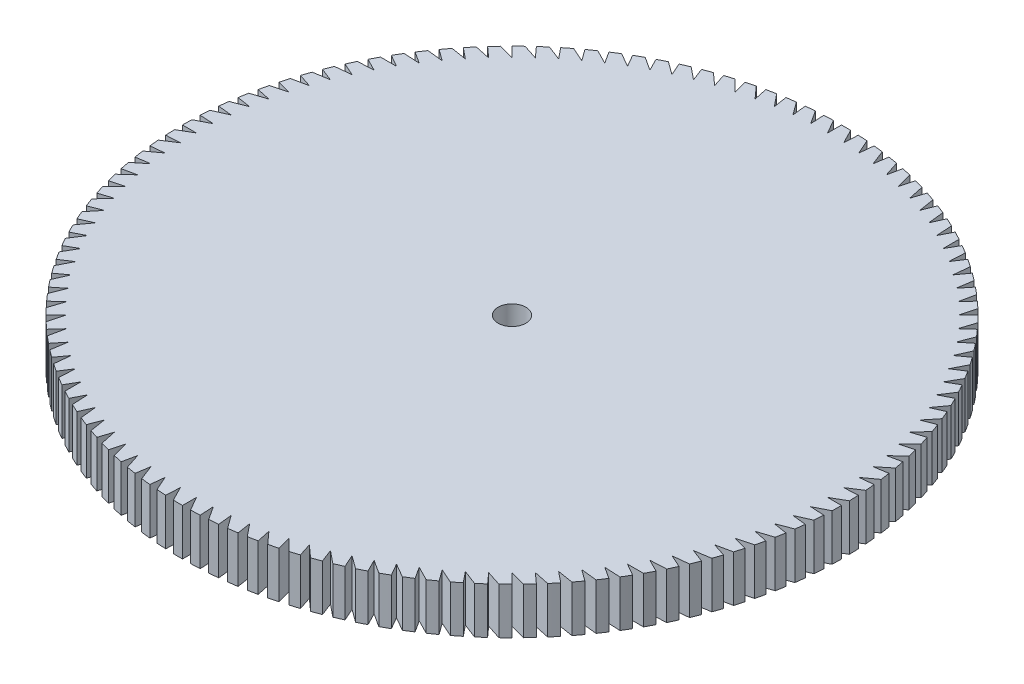
SolidWorks part; units mm, degrees
ref_plane "前视基准面" through (0, 0, 0) normal (0, 0, 1) x (1, 0, 0)
ref_plane "上视基准面" through (0, 0, 0) normal (0, 1, 0) x (1, 0, 0)
ref_plane "右视基准面" through (0, 0, 0) normal (1, 0, 0) x (0, 0, -1)
sketch "草图1" plane through (0, 0, 0) normal (0, 1, 0) x (1, 0, 0)
  circle A0 centre (0, 0) radius 71
  dimension "D1" = 142
extrude "凸台-拉伸1" add sketch "草图1" along normal blind 10
sketch "草图2" plane through (0, 10, 0) normal (0, 1, 0) x (1, 0, 0)
  circle A0 centre (0, 0) radius 3
  dimension "D1" = 6
extrude "切除-拉伸1" cut sketch "草图2" against normal blind 10
sketch "草图3" plane through (0, 10, 0) normal (0, 1, 0) x (1, 0, 0)
  line L0 (0, -71) -> (0, -68)
  line L1 (0, -68) -> (1.72, -70.9792)
  line L2 (-3.5588, -67.9068) -> (-1.9971, -70.9719)
  line L3 (-3.7159, -70.9027) -> (-3.5588, -67.9068)
  line L4 (-7.1079, -67.6275) -> (-5.7087, -70.7701)
  line L5 (-7.4215, -70.6111) -> (-7.1079, -67.6275)
  line L6 (-10.6375, -67.1628) -> (-9.4047, -70.3744)
  line L7 (-11.1068, -70.1259) -> (-10.6375, -67.1628)
  line L8 (-14.138, -66.514) -> (-13.075, -69.7857)
  line L9 (-14.7617, -69.4485) -> (-14.138, -66.514)
  line L10 (-17.5997, -65.683) -> (-16.7093, -69.0058)
  line L11 (-18.3762, -68.5807) -> (-17.5997, -65.683)
  line L12 (-21.0132, -64.6718) -> (-20.2979, -68.0367)
  line L13 (-21.9402, -67.525) -> (-21.0132, -64.6718)
  line L14 (-24.369, -63.4835) -> (-23.8309, -66.8812)
  line L15 (-25.4441, -66.2842) -> (-24.369, -63.4835)
  line L16 (-27.6581, -62.1211) -> (-27.2985, -65.5423)
  line L17 (-28.8783, -64.8617) -> (-27.6581, -62.1211)
  line L18 (-30.8714, -60.5884) -> (-30.6913, -64.0238)
  line L19 (-32.2333, -63.2615) -> (-30.8714, -60.5884)
  line L20 (-34, -58.8897) -> (-34, -62.3298)
  line L21 (-35.5, -61.4878) -> (-34, -58.8897)
  line L22 (-37.0355, -57.0296) -> (-37.2155, -60.4649)
  line L23 (-38.6694, -59.5456) -> (-37.0355, -57.0296)
  line L24 (-39.9694, -55.0132) -> (-40.329, -58.4344)
  line L25 (-41.7328, -57.4402) -> (-39.9694, -55.0132)
  line L26 (-42.7938, -52.8459) -> (-43.3319, -56.2436)
  line L27 (-44.6817, -55.1774) -> (-42.7938, -52.8459)
  line L28 (-45.5009, -50.5338) -> (-46.2161, -53.8987)
  line L29 (-47.5083, -52.7633) -> (-45.5009, -50.5338)
  line L30 (-48.0833, -48.0833) -> (-48.9736, -51.4061)
  line L31 (-50.2046, -50.2046) -> (-48.0833, -48.0833)
  line L32 (-50.5338, -45.5009) -> (-51.5969, -48.7726)
  line L33 (-52.7633, -47.5083) -> (-50.5338, -45.5009)
  line L34 (-52.8459, -42.7938) -> (-54.0787, -46.0053)
  line L35 (-55.1774, -44.6817) -> (-52.8459, -42.7938)
  line L36 (-55.0132, -39.9694) -> (-56.4123, -43.112)
  line L37 (-57.4402, -41.7328) -> (-55.0132, -39.9694)
  line L38 (-57.0296, -37.0355) -> (-58.5913, -40.1006)
  line L39 (-59.5456, -38.6694) -> (-57.0296, -37.0355)
  line L40 (-58.8897, -34) -> (-60.6097, -36.9792)
  line L41 (-61.4878, -35.5) -> (-58.8897, -34)
  line L42 (-60.5884, -30.8714) -> (-62.462, -33.7564)
  line L43 (-63.2615, -32.2333) -> (-60.5884, -30.8714)
  line L44 (-62.1211, -27.6581) -> (-64.1431, -30.4411)
  line L45 (-64.8617, -28.8783) -> (-62.1211, -27.6581)
  line L46 (-63.4835, -24.369) -> (-65.6484, -27.0424)
  line L47 (-66.2842, -25.4441) -> (-63.4835, -24.369)
  line L48 (-64.6718, -21.0132) -> (-66.9737, -23.5696)
  line L49 (-67.525, -21.9402) -> (-64.6718, -21.0132)
  line L50 (-65.683, -17.5997) -> (-68.1154, -20.0322)
  line L51 (-68.5807, -18.3762) -> (-65.683, -17.5997)
  line L52 (-66.514, -14.138) -> (-69.0705, -16.4398)
  line L53 (-69.4485, -14.7617) -> (-66.514, -14.138)
  line L54 (-67.1628, -10.6375) -> (-69.8362, -12.8024)
  line L55 (-70.1259, -11.1068) -> (-67.1628, -10.6375)
  line L56 (-67.6275, -7.1079) -> (-70.4105, -9.1299)
  line L57 (-70.6111, -7.4215) -> (-67.6275, -7.1079)
  line L58 (-67.9068, -3.5588) -> (-70.7919, -5.4324)
  line L59 (-70.9027, -3.7159) -> (-67.9068, -3.5588)
  line L60 (-68, 0) -> (-70.9792, -1.72)
  line L61 (-71, 0) -> (-68, 0)
  line L62 (-67.9068, 3.5588) -> (-70.9719, 1.9971)
  line L63 (-70.9027, 3.7159) -> (-67.9068, 3.5588)
  line L64 (-67.6275, 7.1079) -> (-70.7701, 5.7087)
  line L65 (-70.6111, 7.4215) -> (-67.6275, 7.1079)
  line L66 (-67.1628, 10.6375) -> (-70.3744, 9.4047)
  line L67 (-70.1259, 11.1068) -> (-67.1628, 10.6375)
  line L68 (-66.514, 14.138) -> (-69.7857, 13.075)
  line L69 (-69.4485, 14.7617) -> (-66.514, 14.138)
  line L70 (-65.683, 17.5997) -> (-69.0058, 16.7093)
  line L71 (-68.5807, 18.3762) -> (-65.683, 17.5997)
  line L72 (-64.6718, 21.0132) -> (-68.0367, 20.2979)
  line L73 (-67.525, 21.9402) -> (-64.6718, 21.0132)
  line L74 (-63.4835, 24.369) -> (-66.8812, 23.8309)
  line L75 (-66.2842, 25.4441) -> (-63.4835, 24.369)
  line L76 (-62.1211, 27.6581) -> (-65.5423, 27.2985)
  line L77 (-64.8617, 28.8783) -> (-62.1211, 27.6581)
  line L78 (-60.5884, 30.8714) -> (-64.0238, 30.6913)
  line L79 (-63.2615, 32.2333) -> (-60.5884, 30.8714)
  line L80 (-58.8897, 34) -> (-62.3298, 34)
  line L81 (-61.4878, 35.5) -> (-58.8897, 34)
  line L82 (-57.0296, 37.0355) -> (-60.4649, 37.2155)
  line L83 (-59.5456, 38.6694) -> (-57.0296, 37.0355)
  line L84 (-55.0132, 39.9694) -> (-58.4344, 40.329)
  line L85 (-57.4402, 41.7328) -> (-55.0132, 39.9694)
  line L86 (-52.8459, 42.7938) -> (-56.2436, 43.3319)
  line L87 (-55.1774, 44.6817) -> (-52.8459, 42.7938)
  line L88 (-50.5338, 45.5009) -> (-53.8987, 46.2161)
  line L89 (-52.7633, 47.5083) -> (-50.5338, 45.5009)
  line L90 (-48.0833, 48.0833) -> (-51.4061, 48.9736)
  line L91 (-50.2046, 50.2046) -> (-48.0833, 48.0833)
  line L92 (-45.5009, 50.5338) -> (-48.7726, 51.5969)
  line L93 (-47.5083, 52.7633) -> (-45.5009, 50.5338)
  line L94 (-42.7938, 52.8459) -> (-46.0053, 54.0787)
  line L95 (-44.6817, 55.1774) -> (-42.7938, 52.8459)
  line L96 (-39.9694, 55.0132) -> (-43.112, 56.4123)
  line L97 (-41.7328, 57.4402) -> (-39.9694, 55.0132)
  line L98 (-37.0355, 57.0296) -> (-40.1006, 58.5913)
  line L99 (-38.6694, 59.5456) -> (-37.0355, 57.0296)
  line L100 (-34, 58.8897) -> (-36.9792, 60.6097)
  line L101 (-35.5, 61.4878) -> (-34, 58.8897)
  line L102 (-30.8714, 60.5884) -> (-33.7564, 62.462)
  line L103 (-32.2333, 63.2615) -> (-30.8714, 60.5884)
  line L104 (-27.6581, 62.1211) -> (-30.4411, 64.1431)
  line L105 (-28.8783, 64.8617) -> (-27.6581, 62.1211)
  line L106 (-24.369, 63.4835) -> (-27.0424, 65.6484)
  line L107 (-25.4441, 66.2842) -> (-24.369, 63.4835)
  line L108 (-21.0132, 64.6718) -> (-23.5696, 66.9737)
  line L109 (-21.9402, 67.525) -> (-21.0132, 64.6718)
  line L110 (-17.5997, 65.683) -> (-20.0322, 68.1154)
  line L111 (-18.3762, 68.5807) -> (-17.5997, 65.683)
  line L112 (-14.138, 66.514) -> (-16.4398, 69.0705)
  line L113 (-14.7617, 69.4485) -> (-14.138, 66.514)
  line L114 (-10.6375, 67.1628) -> (-12.8024, 69.8362)
  line L115 (-11.1068, 70.1259) -> (-10.6375, 67.1628)
  line L116 (-7.1079, 67.6275) -> (-9.1299, 70.4105)
  line L117 (-7.4215, 70.6111) -> (-7.1079, 67.6275)
  line L118 (-3.5588, 67.9068) -> (-5.4324, 70.7919)
  line L119 (-3.7159, 70.9027) -> (-3.5588, 67.9068)
  line L120 (0, 68) -> (-1.72, 70.9792)
  line L121 (0, 71) -> (0, 68)
  line L122 (3.5588, 67.9068) -> (1.9971, 70.9719)
  line L123 (3.7159, 70.9027) -> (3.5588, 67.9068)
  line L124 (7.1079, 67.6275) -> (5.7087, 70.7701)
  line L125 (7.4215, 70.6111) -> (7.1079, 67.6275)
  line L126 (10.6375, 67.1628) -> (9.4047, 70.3744)
  line L127 (11.1068, 70.1259) -> (10.6375, 67.1628)
  line L128 (14.138, 66.514) -> (13.075, 69.7857)
  line L129 (14.7617, 69.4485) -> (14.138, 66.514)
  line L130 (17.5997, 65.683) -> (16.7093, 69.0058)
  line L131 (18.3762, 68.5807) -> (17.5997, 65.683)
  line L132 (21.0132, 64.6718) -> (20.2979, 68.0367)
  line L133 (21.9402, 67.525) -> (21.0132, 64.6718)
  line L134 (24.369, 63.4835) -> (23.8309, 66.8812)
  line L135 (25.4441, 66.2842) -> (24.369, 63.4835)
  line L136 (27.6581, 62.1211) -> (27.2985, 65.5423)
  line L137 (28.8783, 64.8617) -> (27.6581, 62.1211)
  line L138 (30.8714, 60.5884) -> (30.6913, 64.0238)
  line L139 (32.2333, 63.2615) -> (30.8714, 60.5884)
  line L140 (34, 58.8897) -> (34, 62.3298)
  line L141 (35.5, 61.4878) -> (34, 58.8897)
  line L142 (37.0355, 57.0296) -> (37.2155, 60.4649)
  line L143 (38.6694, 59.5456) -> (37.0355, 57.0296)
  line L144 (39.9694, 55.0132) -> (40.329, 58.4344)
  line L145 (41.7328, 57.4402) -> (39.9694, 55.0132)
  line L146 (42.7938, 52.8459) -> (43.3319, 56.2436)
  line L147 (44.6817, 55.1774) -> (42.7938, 52.8459)
  line L148 (45.5009, 50.5338) -> (46.2161, 53.8987)
  line L149 (47.5083, 52.7633) -> (45.5009, 50.5338)
  line L150 (48.0833, 48.0833) -> (48.9736, 51.4061)
  line L151 (50.2046, 50.2046) -> (48.0833, 48.0833)
  line L152 (50.5338, 45.5009) -> (51.5969, 48.7726)
  line L153 (52.7633, 47.5083) -> (50.5338, 45.5009)
  line L154 (52.8459, 42.7938) -> (54.0787, 46.0053)
  line L155 (55.1774, 44.6817) -> (52.8459, 42.7938)
  line L156 (55.0132, 39.9694) -> (56.4123, 43.112)
  line L157 (57.4402, 41.7328) -> (55.0132, 39.9694)
  line L158 (57.0296, 37.0355) -> (58.5913, 40.1006)
  line L159 (59.5456, 38.6694) -> (57.0296, 37.0355)
  line L160 (58.8897, 34) -> (60.6097, 36.9792)
  line L161 (61.4878, 35.5) -> (58.8897, 34)
  line L162 (60.5884, 30.8714) -> (62.462, 33.7564)
  line L163 (63.2615, 32.2333) -> (60.5884, 30.8714)
  line L164 (62.1211, 27.6581) -> (64.1431, 30.4411)
  line L165 (64.8617, 28.8783) -> (62.1211, 27.6581)
  line L166 (63.4835, 24.369) -> (65.6484, 27.0424)
  line L167 (66.2842, 25.4441) -> (63.4835, 24.369)
  line L168 (64.6718, 21.0132) -> (66.9737, 23.5696)
  line L169 (67.525, 21.9402) -> (64.6718, 21.0132)
  line L170 (65.683, 17.5997) -> (68.1154, 20.0322)
  line L171 (68.5807, 18.3762) -> (65.683, 17.5997)
  line L172 (66.514, 14.138) -> (69.0705, 16.4398)
  line L173 (69.4485, 14.7617) -> (66.514, 14.138)
  line L174 (67.1628, 10.6375) -> (69.8362, 12.8024)
  line L175 (70.1259, 11.1068) -> (67.1628, 10.6375)
  line L176 (67.6275, 7.1079) -> (70.4105, 9.1299)
  line L177 (70.6111, 7.4215) -> (67.6275, 7.1079)
  line L178 (67.9068, 3.5588) -> (70.7919, 5.4324)
  line L179 (70.9027, 3.7159) -> (67.9068, 3.5588)
  line L180 (68, 0) -> (70.9792, 1.72)
  line L181 (71, 0) -> (68, 0)
  line L182 (67.9068, -3.5588) -> (70.9719, -1.9971)
  line L183 (70.9027, -3.7159) -> (67.9068, -3.5588)
  line L184 (67.6275, -7.1079) -> (70.7701, -5.7087)
  line L185 (70.6111, -7.4215) -> (67.6275, -7.1079)
  line L186 (67.1628, -10.6375) -> (70.3744, -9.4047)
  line L187 (70.1259, -11.1068) -> (67.1628, -10.6375)
  line L188 (66.514, -14.138) -> (69.7857, -13.075)
  line L189 (69.4485, -14.7617) -> (66.514, -14.138)
  line L190 (65.683, -17.5997) -> (69.0058, -16.7093)
  line L191 (68.5807, -18.3762) -> (65.683, -17.5997)
  line L192 (64.6718, -21.0132) -> (68.0367, -20.2979)
  line L193 (67.525, -21.9402) -> (64.6718, -21.0132)
  line L194 (63.4835, -24.369) -> (66.8812, -23.8309)
  line L195 (66.2842, -25.4441) -> (63.4835, -24.369)
  line L196 (62.1211, -27.6581) -> (65.5423, -27.2985)
  line L197 (64.8617, -28.8783) -> (62.1211, -27.6581)
  line L198 (60.5884, -30.8714) -> (64.0238, -30.6913)
  line L199 (63.2615, -32.2333) -> (60.5884, -30.8714)
  line L200 (58.8897, -34) -> (62.3298, -34)
  line L201 (61.4878, -35.5) -> (58.8897, -34)
  line L202 (57.0296, -37.0355) -> (60.4649, -37.2155)
  line L203 (59.5456, -38.6694) -> (57.0296, -37.0355)
  line L204 (55.0132, -39.9694) -> (58.4344, -40.329)
  line L205 (57.4402, -41.7328) -> (55.0132, -39.9694)
  line L206 (52.8459, -42.7938) -> (56.2436, -43.3319)
  line L207 (55.1774, -44.6817) -> (52.8459, -42.7938)
  line L208 (50.5338, -45.5009) -> (53.8987, -46.2161)
  line L209 (52.7633, -47.5083) -> (50.5338, -45.5009)
  line L210 (48.0833, -48.0833) -> (51.4061, -48.9736)
  line L211 (50.2046, -50.2046) -> (48.0833, -48.0833)
  line L212 (45.5009, -50.5338) -> (48.7726, -51.5969)
  line L213 (47.5083, -52.7633) -> (45.5009, -50.5338)
  line L214 (42.7938, -52.8459) -> (46.0053, -54.0787)
  line L215 (44.6817, -55.1774) -> (42.7938, -52.8459)
  line L216 (39.9694, -55.0132) -> (43.112, -56.4123)
  line L217 (41.7328, -57.4402) -> (39.9694, -55.0132)
  line L218 (37.0355, -57.0296) -> (40.1006, -58.5913)
  line L219 (38.6694, -59.5456) -> (37.0355, -57.0296)
  line L220 (34, -58.8897) -> (36.9792, -60.6097)
  line L221 (35.5, -61.4878) -> (34, -58.8897)
  line L222 (30.8714, -60.5884) -> (33.7564, -62.462)
  line L223 (32.2333, -63.2615) -> (30.8714, -60.5884)
  line L224 (27.6581, -62.1211) -> (30.4411, -64.1431)
  line L225 (28.8783, -64.8617) -> (27.6581, -62.1211)
  line L226 (24.369, -63.4835) -> (27.0424, -65.6484)
  line L227 (25.4441, -66.2842) -> (24.369, -63.4835)
  line L228 (21.0132, -64.6718) -> (23.5696, -66.9737)
  line L229 (21.9402, -67.525) -> (21.0132, -64.6718)
  line L230 (17.5997, -65.683) -> (20.0322, -68.1154)
  line L231 (18.3762, -68.5807) -> (17.5997, -65.683)
  line L232 (14.138, -66.514) -> (16.4398, -69.0705)
  line L233 (14.7617, -69.4485) -> (14.138, -66.514)
  line L234 (10.6375, -67.1628) -> (12.8024, -69.8362)
  line L235 (11.1068, -70.1259) -> (10.6375, -67.1628)
  line L236 (7.1079, -67.6275) -> (9.1299, -70.4105)
  line L237 (7.4215, -70.6111) -> (7.1079, -67.6275)
  line L238 (3.5588, -67.9068) -> (5.4324, -70.7919)
  line L239 (3.7159, -70.9027) -> (3.5588, -67.9068)
  circle A0 centre (0, 0) radius 71 construction
  arc A1 (0, -71) -> (1.72, -70.9792) centre (0, 0) ccw
  arc A2 (-3.7159, -70.9027) -> (-1.9971, -70.9719) centre (0, 0) ccw
  arc A3 (-7.4215, -70.6111) -> (-5.7087, -70.7701) centre (0, 0) ccw
  arc A4 (-11.1068, -70.1259) -> (-9.4047, -70.3744) centre (0, 0) ccw
  arc A5 (-14.7617, -69.4485) -> (-13.075, -69.7857) centre (0, 0) ccw
  arc A6 (-18.3762, -68.5807) -> (-16.7093, -69.0058) centre (0, 0) ccw
  arc A7 (-21.9402, -67.525) -> (-20.2979, -68.0367) centre (0, 0) ccw
  arc A8 (-25.4441, -66.2842) -> (-23.8309, -66.8812) centre (0, 0) ccw
  arc A9 (-28.8783, -64.8617) -> (-27.2985, -65.5423) centre (0, 0) ccw
  arc A10 (-32.2333, -63.2615) -> (-30.6913, -64.0238) centre (0, 0) ccw
  arc A11 (-35.5, -61.4878) -> (-34, -62.3298) centre (0, 0) ccw
  arc A12 (-38.6694, -59.5456) -> (-37.2155, -60.4649) centre (0, 0) ccw
  arc A13 (-41.7328, -57.4402) -> (-40.329, -58.4344) centre (0, 0) ccw
  arc A14 (-44.6817, -55.1774) -> (-43.3319, -56.2436) centre (0, 0) ccw
  arc A15 (-47.5083, -52.7633) -> (-46.2161, -53.8987) centre (0, 0) ccw
  arc A16 (-50.2046, -50.2046) -> (-48.9736, -51.4061) centre (0, 0) ccw
  arc A17 (-52.7633, -47.5083) -> (-51.5969, -48.7726) centre (0, 0) ccw
  arc A18 (-55.1774, -44.6817) -> (-54.0787, -46.0053) centre (0, 0) ccw
  arc A19 (-57.4402, -41.7328) -> (-56.4123, -43.112) centre (0, 0) ccw
  arc A20 (-59.5456, -38.6694) -> (-58.5913, -40.1006) centre (0, 0) ccw
  arc A21 (-61.4878, -35.5) -> (-60.6097, -36.9792) centre (0, 0) ccw
  arc A22 (-63.2615, -32.2333) -> (-62.462, -33.7564) centre (0, 0) ccw
  arc A23 (-64.8617, -28.8783) -> (-64.1431, -30.4411) centre (0, 0) ccw
  arc A24 (-66.2842, -25.4441) -> (-65.6484, -27.0424) centre (0, 0) ccw
  arc A25 (-67.525, -21.9402) -> (-66.9737, -23.5696) centre (0, 0) ccw
  arc A26 (-68.5807, -18.3762) -> (-68.1154, -20.0322) centre (0, 0) ccw
  arc A27 (-69.4485, -14.7617) -> (-69.0705, -16.4398) centre (0, 0) ccw
  arc A28 (-70.1259, -11.1068) -> (-69.8362, -12.8024) centre (0, 0) ccw
  arc A29 (-70.6111, -7.4215) -> (-70.4105, -9.1299) centre (0, 0) ccw
  arc A30 (-70.9027, -3.7159) -> (-70.7919, -5.4324) centre (0, 0) ccw
  arc A31 (-71, 0) -> (-70.9792, -1.72) centre (0, 0) ccw
  arc A32 (-70.9027, 3.7159) -> (-70.9719, 1.9971) centre (0, 0) ccw
  arc A33 (-70.6111, 7.4215) -> (-70.7701, 5.7087) centre (0, 0) ccw
  arc A34 (-70.1259, 11.1068) -> (-70.3744, 9.4047) centre (0, 0) ccw
  arc A35 (-69.4485, 14.7617) -> (-69.7857, 13.075) centre (0, 0) ccw
  arc A36 (-68.5807, 18.3762) -> (-69.0058, 16.7093) centre (0, 0) ccw
  arc A37 (-67.525, 21.9402) -> (-68.0367, 20.2979) centre (0, 0) ccw
  arc A38 (-66.2842, 25.4441) -> (-66.8812, 23.8309) centre (0, 0) ccw
  arc A39 (-64.8617, 28.8783) -> (-65.5423, 27.2985) centre (0, 0) ccw
  arc A40 (-63.2615, 32.2333) -> (-64.0238, 30.6913) centre (0, 0) ccw
  arc A41 (-61.4878, 35.5) -> (-62.3298, 34) centre (0, 0) ccw
  arc A42 (-59.5456, 38.6694) -> (-60.4649, 37.2155) centre (0, 0) ccw
  arc A43 (-57.4402, 41.7328) -> (-58.4344, 40.329) centre (0, 0) ccw
  arc A44 (-55.1774, 44.6817) -> (-56.2436, 43.3319) centre (0, 0) ccw
  arc A45 (-52.7633, 47.5083) -> (-53.8987, 46.2161) centre (0, 0) ccw
  arc A46 (-50.2046, 50.2046) -> (-51.4061, 48.9736) centre (0, 0) ccw
  arc A47 (-47.5083, 52.7633) -> (-48.7726, 51.5969) centre (0, 0) ccw
  arc A48 (-44.6817, 55.1774) -> (-46.0053, 54.0787) centre (0, 0) ccw
  arc A49 (-41.7328, 57.4402) -> (-43.112, 56.4123) centre (0, 0) ccw
  arc A50 (-38.6694, 59.5456) -> (-40.1006, 58.5913) centre (0, 0) ccw
  arc A51 (-35.5, 61.4878) -> (-36.9792, 60.6097) centre (0, 0) ccw
  arc A52 (-32.2333, 63.2615) -> (-33.7564, 62.462) centre (0, 0) ccw
  arc A53 (-28.8783, 64.8617) -> (-30.4411, 64.1431) centre (0, 0) ccw
  arc A54 (-25.4441, 66.2842) -> (-27.0424, 65.6484) centre (0, 0) ccw
  arc A55 (-21.9402, 67.525) -> (-23.5696, 66.9737) centre (0, 0) ccw
  arc A56 (-18.3762, 68.5807) -> (-20.0322, 68.1154) centre (0, 0) ccw
  arc A57 (-14.7617, 69.4485) -> (-16.4398, 69.0705) centre (0, 0) ccw
  arc A58 (-11.1068, 70.1259) -> (-12.8024, 69.8362) centre (0, 0) ccw
  arc A59 (-7.4215, 70.6111) -> (-9.1299, 70.4105) centre (0, 0) ccw
  arc A60 (-3.7159, 70.9027) -> (-5.4324, 70.7919) centre (0, 0) ccw
  arc A61 (0, 71) -> (-1.72, 70.9792) centre (0, 0) ccw
  arc A62 (3.7159, 70.9027) -> (1.9971, 70.9719) centre (0, 0) ccw
  arc A63 (7.4215, 70.6111) -> (5.7087, 70.7701) centre (0, 0) ccw
  arc A64 (11.1068, 70.1259) -> (9.4047, 70.3744) centre (0, 0) ccw
  arc A65 (14.7617, 69.4485) -> (13.075, 69.7857) centre (0, 0) ccw
  arc A66 (18.3762, 68.5807) -> (16.7093, 69.0058) centre (0, 0) ccw
  arc A67 (21.9402, 67.525) -> (20.2979, 68.0367) centre (0, 0) ccw
  arc A68 (25.4441, 66.2842) -> (23.8309, 66.8812) centre (0, 0) ccw
  arc A69 (28.8783, 64.8617) -> (27.2985, 65.5423) centre (0, 0) ccw
  arc A70 (32.2333, 63.2615) -> (30.6913, 64.0238) centre (0, 0) ccw
  arc A71 (35.5, 61.4878) -> (34, 62.3298) centre (0, 0) ccw
  arc A72 (38.6694, 59.5456) -> (37.2155, 60.4649) centre (0, 0) ccw
  arc A73 (41.7328, 57.4402) -> (40.329, 58.4344) centre (0, 0) ccw
  arc A74 (44.6817, 55.1774) -> (43.3319, 56.2436) centre (0, 0) ccw
  arc A75 (47.5083, 52.7633) -> (46.2161, 53.8987) centre (0, 0) ccw
  arc A76 (50.2046, 50.2046) -> (48.9736, 51.4061) centre (0, 0) ccw
  arc A77 (52.7633, 47.5083) -> (51.5969, 48.7726) centre (0, 0) ccw
  arc A78 (55.1774, 44.6817) -> (54.0787, 46.0053) centre (0, 0) ccw
  arc A79 (57.4402, 41.7328) -> (56.4123, 43.112) centre (0, 0) ccw
  arc A80 (59.5456, 38.6694) -> (58.5913, 40.1006) centre (0, 0) ccw
  arc A81 (61.4878, 35.5) -> (60.6097, 36.9792) centre (0, 0) ccw
  arc A82 (63.2615, 32.2333) -> (62.462, 33.7564) centre (0, 0) ccw
  arc A83 (64.8617, 28.8783) -> (64.1431, 30.4411) centre (0, 0) ccw
  arc A84 (66.2842, 25.4441) -> (65.6484, 27.0424) centre (0, 0) ccw
  arc A85 (67.525, 21.9402) -> (66.9737, 23.5696) centre (0, 0) ccw
  arc A86 (68.5807, 18.3762) -> (68.1154, 20.0322) centre (0, 0) ccw
  arc A87 (69.4485, 14.7617) -> (69.0705, 16.4398) centre (0, 0) ccw
  arc A88 (70.1259, 11.1068) -> (69.8362, 12.8024) centre (0, 0) ccw
  arc A89 (70.6111, 7.4215) -> (70.4105, 9.1299) centre (0, 0) ccw
  arc A90 (70.9027, 3.7159) -> (70.7919, 5.4324) centre (0, 0) ccw
  arc A91 (71, 0) -> (70.9792, 1.72) centre (0, 0) ccw
  arc A92 (70.9027, -3.7159) -> (70.9719, -1.9971) centre (0, 0) ccw
  arc A93 (70.6111, -7.4215) -> (70.7701, -5.7087) centre (0, 0) ccw
  arc A94 (70.1259, -11.1068) -> (70.3744, -9.4047) centre (0, 0) ccw
  arc A95 (69.4485, -14.7617) -> (69.7857, -13.075) centre (0, 0) ccw
  arc A96 (68.5807, -18.3762) -> (69.0058, -16.7093) centre (0, 0) ccw
  arc A97 (67.525, -21.9402) -> (68.0367, -20.2979) centre (0, 0) ccw
  arc A98 (66.2842, -25.4441) -> (66.8812, -23.8309) centre (0, 0) ccw
  arc A99 (64.8617, -28.8783) -> (65.5423, -27.2985) centre (0, 0) ccw
  arc A100 (63.2615, -32.2333) -> (64.0238, -30.6913) centre (0, 0) ccw
  arc A101 (61.4878, -35.5) -> (62.3298, -34) centre (0, 0) ccw
  arc A102 (59.5456, -38.6694) -> (60.4649, -37.2155) centre (0, 0) ccw
  arc A103 (57.4402, -41.7328) -> (58.4344, -40.329) centre (0, 0) ccw
  arc A104 (55.1774, -44.6817) -> (56.2436, -43.3319) centre (0, 0) ccw
  arc A105 (52.7633, -47.5083) -> (53.8987, -46.2161) centre (0, 0) ccw
  arc A106 (50.2046, -50.2046) -> (51.4061, -48.9736) centre (0, 0) ccw
  arc A107 (47.5083, -52.7633) -> (48.7726, -51.5969) centre (0, 0) ccw
  arc A108 (44.6817, -55.1774) -> (46.0053, -54.0787) centre (0, 0) ccw
  arc A109 (41.7328, -57.4402) -> (43.112, -56.4123) centre (0, 0) ccw
  arc A110 (38.6694, -59.5456) -> (40.1006, -58.5913) centre (0, 0) ccw
  arc A111 (35.5, -61.4878) -> (36.9792, -60.6097) centre (0, 0) ccw
  arc A112 (32.2333, -63.2615) -> (33.7564, -62.462) centre (0, 0) ccw
  arc A113 (28.8783, -64.8617) -> (30.4411, -64.1431) centre (0, 0) ccw
  arc A114 (25.4441, -66.2842) -> (27.0424, -65.6484) centre (0, 0) ccw
  arc A115 (21.9402, -67.525) -> (23.5696, -66.9737) centre (0, 0) ccw
  arc A116 (18.3762, -68.5807) -> (20.0322, -68.1154) centre (0, 0) ccw
  arc A117 (14.7617, -69.4485) -> (16.4398, -69.0705) centre (0, 0) ccw
  arc A118 (11.1068, -70.1259) -> (12.8024, -69.8362) centre (0, 0) ccw
  arc A119 (7.4215, -70.6111) -> (9.1299, -70.4105) centre (0, 0) ccw
  arc A120 (3.7159, -70.9027) -> (5.4324, -70.7919) centre (0, 0) ccw
  point P367 (0, 0)
  dimension "D1" = 3
  dimension "D2" = 30
  dimension "D3" = 120
extrude "切除-拉伸2" cut sketch "草图3" against normal through all
equation "\"Z\"=10"
